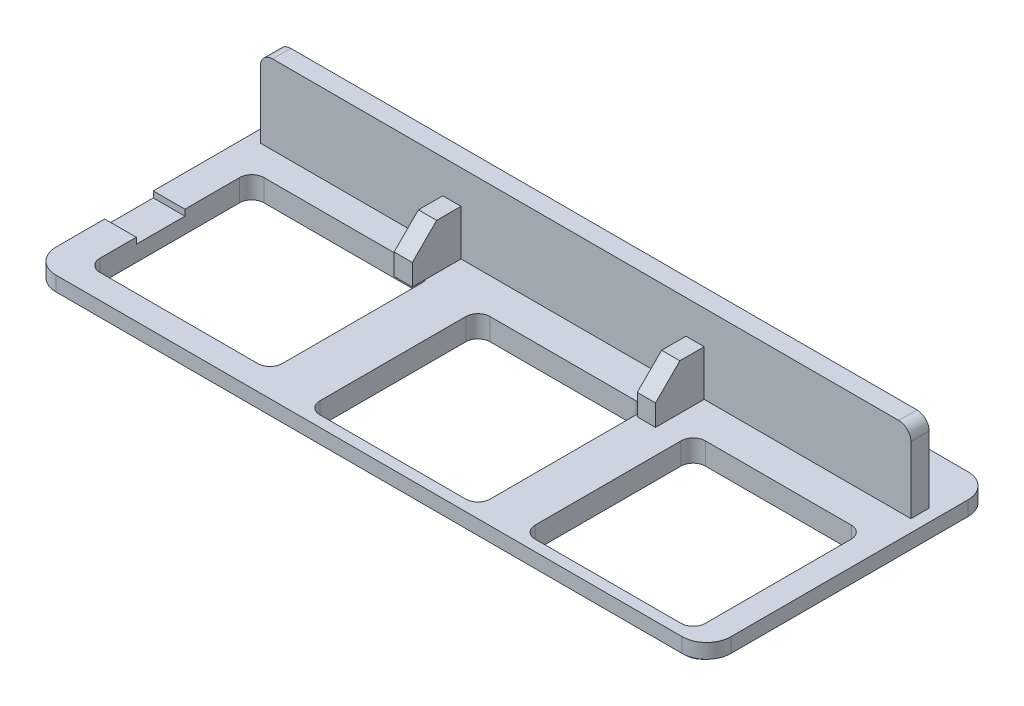
SolidWorks part; units mm, degrees
ref_plane "前视基准面" through (0, 0, 0) normal (0, 0, 1) x (1, 0, 0)
ref_plane "上视基准面" through (0, 0, 0) normal (0, 1, 0) x (1, 0, 0)
ref_plane "右视基准面" through (0, 0, 0) normal (1, 0, 0) x (0, 0, -1)
sketch "草图1" plane through (0, 0, 0) normal (0, 1, 0) x (1, 0, 0)
  line L1 (-27.75, 11.75) -> (27.75, 11.75)
  line L2 (-27.75, 11.75) -> (-27.75, -11.75)
  line L3 (-27.75, -11.75) -> (27.75, -11.75)
  line L4 (27.75, 11.75) -> (27.75, -11.75)
  line L5 (-27.75, 11.75) -> (27.75, -11.75) construction
  line L6 (-27.75, -11.75) -> (27.75, 11.75) construction
  point P0 (0, 0)
  dimension "D1" = 23.5
  dimension "D2" = 55.5
extrude "凸台-拉伸1" add sketch "草图1" along normal blind 1.2
fillet "圆角1" radius 2 4 edges at (-27.75, 0.6, 11.75) (27.75, 0.6, 11.75) (-27.75, 0.6, -11.75) (27.75, 0.6, -11.75)
sketch "草图2" plane through (0, 0, 0) normal (0, -1, 0) x (1, 0, 0)
  line L0 (-27.75, -9.75) -> (-27.75, 9.75) construction
  line L1 (-26.85, 11.15) -> (26.85, 11.15)
  line L2 (-26.85, 11.15) -> (-26.85, -11.15)
  line L3 (-26.85, -11.15) -> (26.85, -11.15)
  line L4 (26.85, 11.15) -> (26.85, -11.15)
  line L5 (27.75, 9.75) -> (27.75, -9.75) construction
  line L6 (-25.75, 11.75) -> (25.75, 11.75) construction
  line L7 (25.75, -11.75) -> (-25.75, -11.75) construction
  dimension "D1" = 0.9
  dimension "D2" = 0.9
  dimension "D3" = 0.6
  dimension "D4" = 0.6
extrude "凸台-拉伸2" add sketch "草图2" along normal blind 0.6
sketch "草图3" plane through (0, -0.6, 0) normal (0, -1, 0) x (1, 0, 0)
  line L1 (-25.15, 9.75) -> (-10.15, 9.75)
  line L2 (-25.15, 9.75) -> (-25.15, -3.75)
  line L3 (-25.15, -3.75) -> (-10.15, -3.75)
  line L4 (-10.15, 9.75) -> (-10.15, -3.75)
  line L5 (-5.95, 10.85) -> (8.05, 10.85)
  line L6 (-5.95, 10.85) -> (-5.95, -3.15)
  line L7 (-5.95, -3.15) -> (8.05, -3.15)
  line L8 (8.05, 10.85) -> (8.05, -3.15)
  line L9 (11.75, 10.85) -> (25.75, 10.85)
  line L10 (11.75, 10.85) -> (11.75, -3.15)
  line L11 (11.75, -3.15) -> (25.75, -3.15)
  line L12 (25.75, 10.85) -> (25.75, -3.15)
  line L15 (-27.75, -9.75) -> (-27.75, 9.75) construction
  line L16 (-25.75, 11.75) -> (25.75, 11.75) construction
  line L17 (27.75, 9.75) -> (27.75, -9.75) construction
  point P18 (0, 0)
  point P19 (0, 0)
  point P20 (0, 0)
  dimension "D1" = 15
  dimension "D2" = 14
  dimension "D3" = 14
  dimension "D4" = 2.6
  dimension "D5" = 2
  dimension "D6" = 21.8
  dimension "D7" = 14
  dimension "D8" = 2
  dimension "D9" = 0.9
  dimension "D10" = 13.5
extrude "切除-拉伸1" cut sketch "草图3" against normal blind 3
fillet "圆角2" radius 1 12 edges at (-25.15, 0.3, 9.75) (-10.15, 0.3, 9.75) (-5.95, 0.3, 10.85) (8.05, 0.3, 10.85) (25.75, 0.3, 10.85) (11.75, 0.3, 10.85) (25.75, 0.3, -3.15) (11.75, 0.3, -3.15) (8.05, 0.3, -3.15) (-5.95, 0.3, -3.15) (-10.15, 0.3, -3.75) (-25.15, 0.3, -3.75)
sketch "草图4" plane through (0, 1.2, 0) normal (0, 1, 0) x (1, 0, 0)
  line L0 (-27.75, 9.75) -> (-27.75, -9.75) construction
  line L1 (-12.25, -5.75) -> (-27.75, -5.75)
  line L2 (-12.25, -5.75) -> (-12.25, -1.7526)
  line L3 (-12.25, -1.7526) -> (-27.75, -1.7526)
  line L4 (-27.75, -5.75) -> (-27.75, -1.7526)
  line L5 (-25.75, -11.75) -> (25.75, -11.75) construction
  dimension "D1" = 6
  dimension "D2" = 3.9974
  dimension "D3" = 15.5
extrude "切除-拉伸2" cut sketch "草图4" against normal blind 0.5
sketch "草图5" plane through (0, 1.2, 0) normal (0, 1, 0) x (1, 0, 0)
  line L1 (26.75, 6.0546) -> (-26.75, 6.0546)
  line L2 (26.75, 6.0546) -> (26.75, 7.5546)
  line L3 (26.75, 7.5546) -> (-26.75, 7.5546)
  line L4 (-26.75, 6.0546) -> (-26.75, 7.5546)
  line L6 (-27.75, 9.75) -> (-27.75, -1.7526) construction
  line L7 (27.75, -9.75) -> (27.75, 9.75) construction
  line L8 (25.75, 11.75) -> (-25.75, 11.75) construction
  dimension "D1" = 1.5
  dimension "D2" = 1
  dimension "D3" = 1
  dimension "D4" = 4.1954
extrude "凸台-拉伸3" add sketch "草图5" along normal blind 6.5
fillet "圆角3" radius 1 2 edges at (-26.75, 7.7, -6.8046) (26.75, 7.7, -6.8046)
sketch "草图6" plane through (0, 1.2, 0) normal (0, 1, 0) x (1, 0, 0)
  line L0 (-26.75, 6.0546) -> (26.75, 6.0546) construction
  line L1 (9.75, 6.0546) -> (8.25, 6.0546)
  line L2 (9.75, 6.0546) -> (9.75, 2.0546)
  line L3 (9.75, 2.0546) -> (8.25, 2.0546)
  line L4 (8.25, 6.0546) -> (8.25, 2.0546)
  line L5 (27.75, -9.75) -> (27.75, 9.75) construction
  line L6 (-10.25, 6.0546) -> (-11.75, 6.0546)
  line L7 (-10.25, 6.0546) -> (-10.25, 2.0546)
  line L8 (-10.25, 2.0546) -> (-11.75, 2.0546)
  line L9 (-11.75, 6.0546) -> (-11.75, 2.0546)
  line L10 (-27.75, -5.75) -> (-27.75, -9.75) construction
  dimension "D1" = 4
  dimension "D2" = 1.5
  dimension "D3" = 18
  dimension "D4" = 16
extrude "凸台-拉伸4" add sketch "草图6" along normal blind 3.75
chamfer "倒角1" distance 2 angle 45 2 edges at (-11, 4.95, -2.0546) (9, 4.95, -2.0546)
fillet "圆角4" radius 1.5 4 edges at (-26.85, -0.3, -11.15) (26.85, -0.3, -11.15) (26.85, -0.3, 11.15) (-26.85, -0.3, 11.15)
